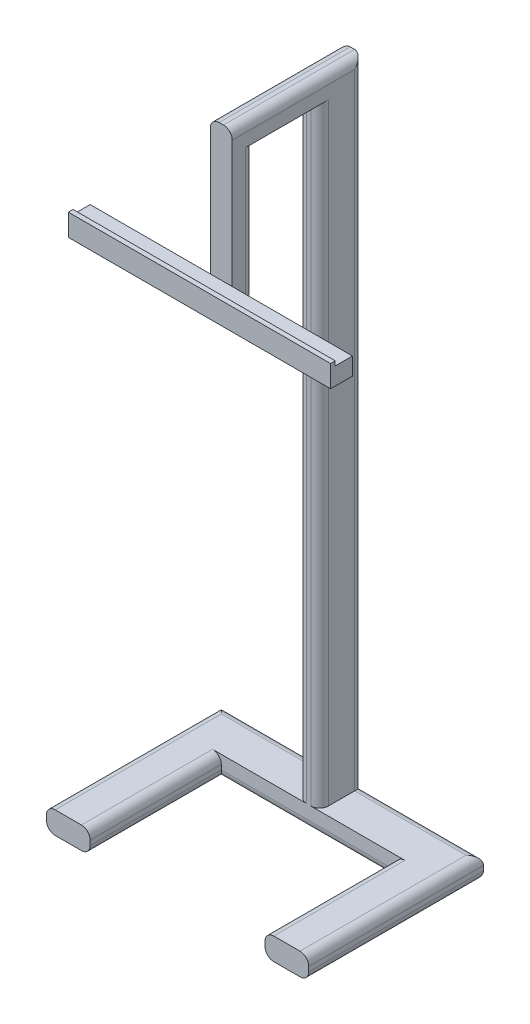
SolidWorks part; units mm, degrees
ref_plane "Front Plane" through (0, 0, 0) normal (0, 0, 1) x (1, 0, 0)
ref_plane "Top Plane" through (0, 0, 0) normal (0, 1, 0) x (1, 0, 0)
ref_plane "Right Plane" through (0, 0, 0) normal (1, 0, 0) x (0, 0, -1)
sketch "Sketch1" plane through (0, 0, 0) normal (0, 1, 0) x (1, 0, 0)
  line L1 (-150, -100) -> (150, -100)
  line L2 (-150, -100) -> (-150, 100)
  line L3 (-150, 100) -> (150, 100)
  line L4 (150, -100) -> (150, 100)
  line L5 (-150, -100) -> (150, 100) construction
  line L6 (-150, 100) -> (150, -100) construction
  point P0 (0, 0)
extrude "Boss-Extrude1" add sketch "Sketch1" along normal blind 25.4
sketch "Sketch2" plane through (0, 25.4, 0) normal (0, 1, 0) x (1, 0, 0)
  line L0 (-150, -100) -> (150, -100) construction
  line L1 (-100, -100) -> (100, -100)
  line L2 (-100, -100) -> (-100, 50)
  line L3 (-100, 50) -> (100, 50)
  line L4 (100, -100) -> (100, 50)
  line L5 (-150, 100) -> (-150, -100) construction
  dimension "D1" = 150
  dimension "D2" = 200
  dimension "D3" = 50
extrude "Cut-Extrude1" cut sketch "Sketch2" against normal blind 25.4
sketch "Sketch3" plane through (0, 25.4, 0) normal (0, 1, 0) x (1, 0, 0)
  line L1 (150, 100) -> (-150, 100) construction
  line L4 (-12.5, 50) -> (12.5, 50)
  line L5 (-12.5, 50) -> (-12.5, 100)
  line L6 (-12.5, 100) -> (12.5, 100)
  line L7 (12.5, 50) -> (12.5, 100)
  line L8 (-12.5, 50) -> (12.5, 100) construction
  line L9 (-12.5, 100) -> (12.5, 50) construction
  point P8 (0, 75)
  dimension "D1" = 25
extrude "Boss-Extrude2" add sketch "Sketch3" along normal blind 724.6
ref_plane "Plane1" through (-12.5, 750, -50) normal (0, -1, 0) x (-1, 0, 0)
sketch "Sketch5" plane through (0, 0, -50) normal (0, 0, 1) x (1, 0, 0)
  line L0 (12.5, 750) -> (12.5, 25.4) construction
  line L1 (-12.5, 750) -> (12.5, 750)
  line L2 (-12.5, 750) -> (-12.5, 725)
  line L3 (-12.5, 725) -> (12.5, 725)
  line L4 (12.5, 750) -> (12.5, 725)
  dimension "D1" = 25
extrude "Boss-Extrude3" add sketch "Sketch5" along normal blind 100
sketch "Sketch6" plane through (0, 725, 0) normal (0, -1, 0) x (1, 0, 0)
  line L0 (12.5, 50) -> (12.5, -50) construction
  line L1 (-12.5, 50) -> (12.5, 50)
  line L2 (-12.5, 50) -> (-12.5, 25)
  line L3 (-12.5, 25) -> (12.5, 25)
  line L4 (12.5, 50) -> (12.5, 25)
  dimension "D1" = 25
extrude "Boss-Extrude4" add sketch "Sketch6" along normal blind 150
sketch "Sketch7" plane through (0, 0, 50) normal (0, 0, 1) x (1, 0, 0)
  line L0 (-12.5, 750) -> (-12.5, 575) construction
  line L1 (-150, 575) -> (150, 575)
  line L2 (-150, 575) -> (-150, 600)
  line L3 (-150, 600) -> (150, 600)
  line L4 (150, 575) -> (150, 600)
  line L5 (12.5, 575) -> (-12.5, 575) construction
  dimension "D1" = 300
  dimension "D2" = 137.5
  dimension "D3" = 25
  dimension "D4" = 0
extrude "Boss-Extrude5" add sketch "Sketch7" along normal blind 25
sketch "Sketch8" plane through (0, 600, 0) normal (0, 1, 0) x (1, 0, 0)
  line L0 (-150, -75) -> (-150, -50) construction
  line L1 (-150, -69.6492) -> (150, -69.6492)
  line L2 (-150, -69.6492) -> (-150, -50)
  line L3 (-150, -50) -> (150, -50)
  line L4 (150, -69.6492) -> (150, -50)
extrude "Cut-Extrude2" cut sketch "Sketch8" against normal blind 5
fillet "Fillet1" radius 10 20 edges at (12.5, 750, -25) (-12.5, 750, -25) (12.5, 650, 25) (-12.5, 650, 25) (-12.5, 375.2, -50) (12.5, 375.2, -50) (12.5, 387.7, -100) (-12.5, 387.7, -100) (-100, 0, 25) (0, 0, -50) (100, 0, 25) (150, 0, 0) (-150, 0, 0) (0, 0, -100) (-81.25, 25.4, -100) (81.25, 25.4, -100) (-150, 25.4, 0) (-100, 25.4, 25) (100, 25.4, 25) (150, 25.4, 0)
